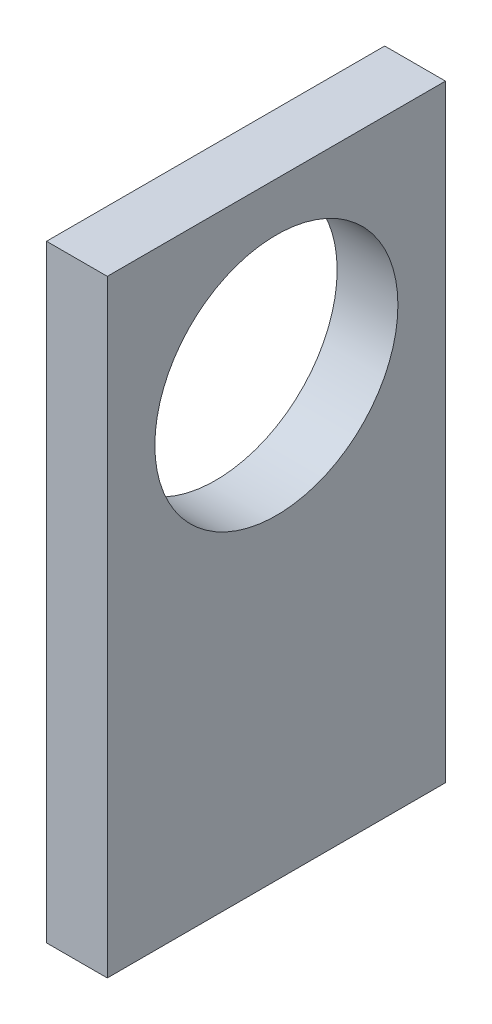
SolidWorks part; units mm, degrees
ref_plane "Front Plane" through (0, 0, 0) normal (0, 0, 1) x (1, 0, 0)
ref_plane "Top Plane" through (0, 0, 0) normal (0, 1, 0) x (1, 0, 0)
ref_plane "Right Plane" through (0, 0, 0) normal (1, 0, 0) x (0, 0, -1)
sketch "Sketch1" plane through (0, 0, 0) normal (1, 0, 0) x (0, 0, -1)
  line L0 (0, 17.78) -> (0, -45.72) construction
  line L1 (-17.6698, 17.78) -> (17.6698, 17.78)
  line L2 (-17.6698, 17.78) -> (-17.6698, -45.72)
  line L3 (-17.6698, -45.72) -> (17.6698, -45.72)
  line L4 (17.6698, 17.78) -> (17.6698, -45.72)
  line L5 (0, 12.7) -> (17.6698, 12.7) construction
  line L6 (12.7, 0) -> (12.7, 17.78) construction
  circle A0 centre (0, 0) radius 12.7
  dimension "D1" = 25.4
  dimension "D4" = 63.5
  dimension "D2" = 5.08
  dimension "D3" = 4.9698
extrude "Boss-Extrude1" add sketch "Sketch1" along normal blind 6.35
